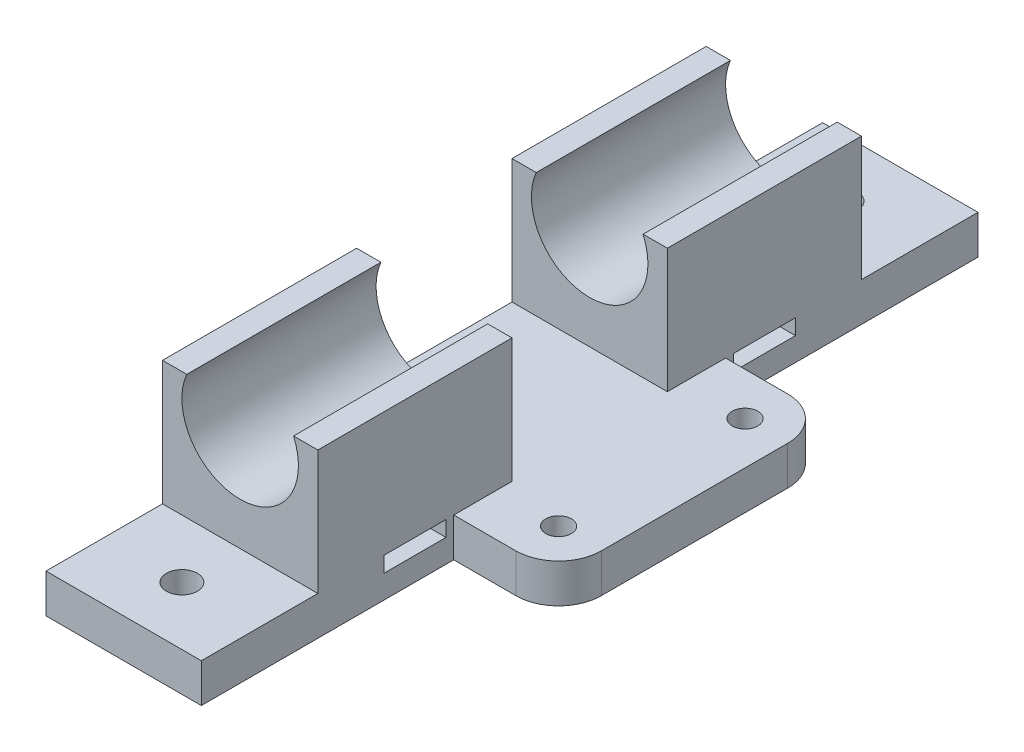
SolidWorks part; units mm, degrees
material "ABS"
ref_plane "Plano frontal" through (0, 0, 0) normal (0, 0, 1) x (1, 0, 0)
ref_plane "Plano superior" through (0, 0, 0) normal (0, 1, 0) x (1, 0, 0)
ref_plane "Plano direito" through (0, 0, 0) normal (1, 0, 0) x (0, 0, -1)
sketch "Esboço1" plane through (0, 0, 0) normal (1, 0, 0) x (0, 0, -1)
  line L0 (0, 14) -> (0, 0) construction
  line L1 (-35, 21) -> (-10, 21)
  line L2 (-35, 21) -> (-35, 0)
  line L3 (-35, 0) -> (35, 0)
  line L4 (35, 21) -> (35, 0)
  line L5 (18.5, 3) -> (26.5, 5) construction
  line L6 (-18.5, 5) -> (-26.5, 5)
  line L7 (-18.5, 5) -> (-18.5, 3)
  line L8 (-18.5, 3) -> (-26.5, 3)
  line L9 (-10, 21) -> (-10, 5)
  line L10 (-26.5, 5) -> (-26.5, 3)
  line L11 (-18.5, 5) -> (-26.5, 3) construction
  line L12 (-18.5, 3) -> (-26.5, 5) construction
  line L13 (18.5, 5) -> (26.5, 3) construction
  line L14 (-10, 5) -> (10, 5)
  line L15 (10, 21) -> (10, 5)
  line L16 (10, 21) -> (35, 21)
  line L17 (26.5, 5) -> (26.5, 3)
  line L18 (18.5, 3) -> (26.5, 3)
  line L19 (18.5, 5) -> (18.5, 3)
  line L20 (18.5, 5) -> (26.5, 5)
  point P0 (0, 0)
  point P1 (-22.5, 4)
  point P18 (0, 5)
  point P21 (22.5, 4)
  point P24 (-22.5, 21)
  dimension "D1" = 8
  dimension "D2" = 21
  dimension "D3" = 70
  dimension "D4" = 2
  dimension "D5" = 25
  dimension "D6" = 5
  dimension "D7" = 4
extrude "Ressalto-extrusão1" add sketch "Esboço1" along normal mid plane 20
sketch "Esboço2" plane through (0, 0, 35) normal (0, 0, 1) x (1, 0, 0)
  line L0 (10, 21) -> (-10, 21) construction
  line L1 (-6.8739, 21) -> (6.8739, 21)
  arc A0 (-6.8739, 21) -> (6.8739, 21) centre (0, 18) ccw
  point P20 (0, 21)
  dimension "D1" = 15
  dimension "D2" = 3
extrude "Corte-extrusão1" cut sketch "Esboço2" against normal up to surface (70 mm away) up to face at (0, 10.5, -35)
sketch "Esboço4" plane through (0, 5, 0) normal (0, 1, 0) x (1, 0, 0)
  line L1 (-10, 0) -> (10, 0) construction
  line L2 (-10, 35) -> (10, 35)
  line L3 (-10, 35) -> (-10, 50)
  line L4 (-10, 50) -> (10, 50)
  line L5 (10, -35) -> (10, -50)
  line L6 (10, 35) -> (10, 50)
  line L7 (-10, -50) -> (10, -50)
  line L8 (-10, 10) -> (-10, -10) construction
  line L9 (10, 10) -> (10, -10) construction
  line L10 (-10, -35) -> (-10, -50)
  line L11 (-10, -35) -> (10, -35)
  line L12 (10, -35) -> (10, 35) construction
  circle A0 centre (0, 42.5) radius 2
  circle A1 centre (0, -42.5) radius 2
  point P13 (0, 50)
  dimension "D3" = 7.5
  dimension "D2" = 4
  dimension "D1" = 100
extrude "Ressalto-extrusão2" add sketch "Esboço4" against normal up to surface (5 mm away) up to face at (0, 0, 0)
sketch "Esboço5" plane through (0, 0, 0) normal (0, -1, 0) x (1, 0, 0)
  line L0 (18, 17.5) -> (10, 17.5)
  line L1 (10, 50) -> (10, -50) construction
  line L2 (10, 17.5) -> (10, -17.5)
  line L3 (10, -17.5) -> (18, -17.5)
  line L4 (23.5, 12) -> (23.5, -12)
  circle A0 centre (18, 12) radius 1.65
  arc A1 (23.5, 12) -> (18, 17.5) centre (18, 12) ccw
  arc A2 (18, -17.5) -> (23.5, -12) centre (18, -12) ccw
  circle A3 centre (18, -12) radius 1.65
  circle A4 centre (18, -12) radius 5 construction
  circle A5 centre (18, 12) radius 5 construction
  point P2 (23.5, 0)
  dimension "D1" = 10
  dimension "D2" = 3.3
  dimension "D3" = 11
  dimension "D5" = 3
  dimension "D4" = 24
extrude "Ressalto-extrusão3" add sketch "Esboço5" against normal blind 5
